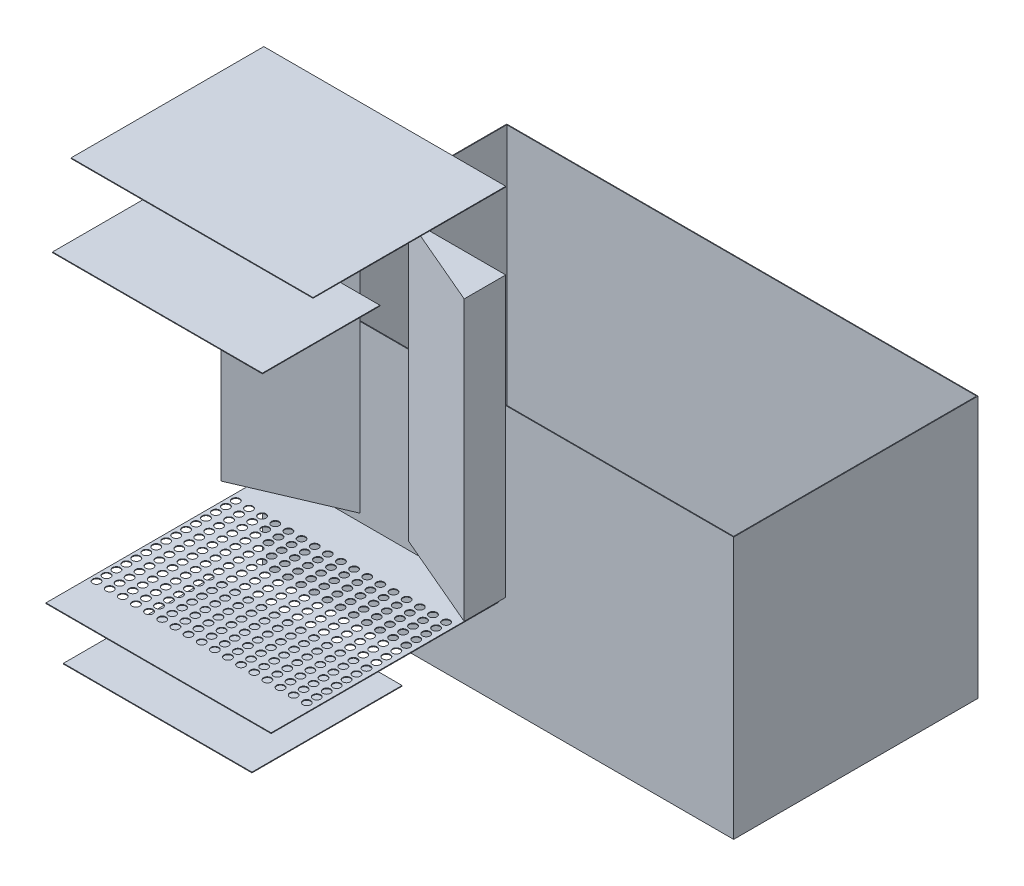
SolidWorks part; units mm, degrees
ref_plane "Спереди" through (0, 0, 0) normal (0, 0, 1) x (1, 0, 0)
ref_plane "Сверху" through (0, 0, 0) normal (0, 1, 0) x (1, 0, 0)
ref_plane "Справа" through (0, 0, 0) normal (1, 0, 0) x (0, 0, -1)
sketch "MASTER_FOOTPRINT" plane through (0, 0, 0) normal (0, 1, 0) x (1, 0, 0)
  line L1 (0, 0) -> (1350, 0)
  line L2 (0, 0) -> (0, 700)
  line L3 (0, 700) -> (1350, 700)
  line L4 (1350, 0) -> (1350, 700)
  dimension "D1" = 1350
  dimension "D2" = 700
extrude "BATH_BASE_PLATE" add sketch "MASTER_FOOTPRINT" along normal blind 750
shell "BATH_SHELL_2MM" thickness 2
sketch "Эскиз1" plane through (0, 0, 0) normal (0, 1, 0) x (1, 0, 0)
  line L1 (80, -220) -> (620, -220)
  line L2 (80, -220) -> (80, -650)
  line L3 (80, -650) -> (620, -650)
  line L4 (620, -220) -> (620, -650)
extrude "INLET_IMPACT_BAFFLE" add sketch "Эскиз1" along normal blind 2 from offset 125 separate body
sketch "Эскиз2" plane through (0, 0, 0) normal (0, 1, 0) x (1, 0, 0)
  line L0 (2, 2) -> (1348, 2) construction
  line L1 (30, 2) -> (675, 2)
  line L2 (30, 2) -> (30, -650)
  line L3 (30, -650) -> (675, -650)
  line L4 (675, 2) -> (675, -650)
  circle A0 centre (48.8235, -125) radius 11
  circle A1 centre (48.8235, -153.5) radius 11
  circle A2 centre (48.8235, -182) radius 11
  circle A3 centre (48.8235, -210.5) radius 11
  circle A4 centre (48.8235, -239) radius 11
  circle A5 centre (48.8235, -267.5) radius 11
  circle A6 centre (48.8235, -296) radius 11
  circle A7 centre (48.8235, -324.5) radius 11
  circle A8 centre (48.8235, -353) radius 11
  circle A9 centre (48.8235, -381.5) radius 11
  circle A10 centre (48.8235, -410) radius 11
  circle A11 centre (48.8235, -438.5) radius 11
  circle A12 centre (48.8235, -467) radius 11
  circle A13 centre (48.8235, -495.5) radius 11
  circle A14 centre (48.8235, -524) radius 11
  circle A15 centre (86.4706, -125) radius 11
  circle A16 centre (86.4706, -153.5) radius 11
  circle A17 centre (86.4706, -182) radius 11
  circle A18 centre (86.4706, -210.5) radius 11
  circle A19 centre (86.4706, -239) radius 11
  circle A20 centre (86.4706, -267.5) radius 11
  circle A21 centre (86.4706, -296) radius 11
  circle A22 centre (86.4706, -324.5) radius 11
  circle A23 centre (86.4706, -353) radius 11
  circle A24 centre (86.4706, -381.5) radius 11
  circle A25 centre (86.4706, -410) radius 11
  circle A26 centre (86.4706, -438.5) radius 11
  circle A27 centre (86.4706, -467) radius 11
  circle A28 centre (86.4706, -495.5) radius 11
  circle A29 centre (86.4706, -524) radius 11
  circle A30 centre (124.1176, -125) radius 11
  circle A31 centre (124.1176, -153.5) radius 11
  circle A32 centre (124.1176, -182) radius 11
  circle A33 centre (124.1176, -210.5) radius 11
  circle A34 centre (124.1176, -239) radius 11
  circle A35 centre (124.1176, -267.5) radius 11
  circle A36 centre (124.1176, -296) radius 11
  circle A37 centre (124.1176, -324.5) radius 11
  circle A38 centre (124.1176, -353) radius 11
  circle A39 centre (124.1176, -381.5) radius 11
  circle A40 centre (124.1176, -410) radius 11
  circle A41 centre (124.1176, -438.5) radius 11
  circle A42 centre (124.1176, -467) radius 11
  circle A43 centre (124.1176, -495.5) radius 11
  circle A44 centre (124.1176, -524) radius 11
  circle A45 centre (161.7647, -125) radius 11
  circle A46 centre (161.7647, -153.5) radius 11
  circle A47 centre (161.7647, -182) radius 11
  circle A48 centre (161.7647, -210.5) radius 11
  circle A49 centre (161.7647, -239) radius 11
  circle A50 centre (161.7647, -267.5) radius 11
  circle A51 centre (161.7647, -296) radius 11
  circle A52 centre (161.7647, -324.5) radius 11
  circle A53 centre (161.7647, -353) radius 11
  circle A54 centre (161.7647, -381.5) radius 11
  circle A55 centre (161.7647, -410) radius 11
  circle A56 centre (161.7647, -438.5) radius 11
  circle A57 centre (161.7647, -467) radius 11
  circle A58 centre (161.7647, -495.5) radius 11
  circle A59 centre (161.7647, -524) radius 11
  circle A60 centre (199.4118, -125) radius 11
  circle A61 centre (199.4118, -153.5) radius 11
  circle A62 centre (199.4118, -182) radius 11
  circle A63 centre (199.4118, -210.5) radius 11
  circle A64 centre (199.4118, -239) radius 11
  circle A65 centre (199.4118, -267.5) radius 11
  circle A66 centre (199.4118, -296) radius 11
  circle A67 centre (199.4118, -324.5) radius 11
  circle A68 centre (199.4118, -353) radius 11
  circle A69 centre (199.4118, -381.5) radius 11
  circle A70 centre (199.4118, -410) radius 11
  circle A71 centre (199.4118, -438.5) radius 11
  circle A72 centre (199.4118, -467) radius 11
  circle A73 centre (199.4118, -495.5) radius 11
  circle A74 centre (199.4118, -524) radius 11
  circle A75 centre (237.0588, -125) radius 11
  circle A76 centre (237.0588, -153.5) radius 11
  circle A77 centre (237.0588, -182) radius 11
  circle A78 centre (237.0588, -210.5) radius 11
  circle A79 centre (237.0588, -239) radius 11
  circle A80 centre (237.0588, -267.5) radius 11
  circle A81 centre (237.0588, -296) radius 11
  circle A82 centre (237.0588, -324.5) radius 11
  circle A83 centre (237.0588, -353) radius 11
  circle A84 centre (237.0588, -381.5) radius 11
  circle A85 centre (237.0588, -410) radius 11
  circle A86 centre (237.0588, -438.5) radius 11
  circle A87 centre (237.0588, -467) radius 11
  circle A88 centre (237.0588, -495.5) radius 11
  circle A89 centre (237.0588, -524) radius 11
  circle A90 centre (274.7059, -125) radius 11
  circle A91 centre (274.7059, -153.5) radius 11
  circle A92 centre (274.7059, -182) radius 11
  circle A93 centre (274.7059, -210.5) radius 11
  circle A94 centre (274.7059, -239) radius 11
  circle A95 centre (274.7059, -267.5) radius 11
  circle A96 centre (274.7059, -296) radius 11
  circle A97 centre (274.7059, -324.5) radius 11
  circle A98 centre (274.7059, -353) radius 11
  circle A99 centre (274.7059, -381.5) radius 11
  circle A100 centre (274.7059, -410) radius 11
  circle A101 centre (274.7059, -438.5) radius 11
  circle A102 centre (274.7059, -467) radius 11
  circle A103 centre (274.7059, -495.5) radius 11
  circle A104 centre (274.7059, -524) radius 11
  circle A105 centre (312.3529, -125) radius 11
  circle A106 centre (312.3529, -153.5) radius 11
  circle A107 centre (312.3529, -182) radius 11
  circle A108 centre (312.3529, -210.5) radius 11
  circle A109 centre (312.3529, -239) radius 11
  circle A110 centre (312.3529, -267.5) radius 11
  circle A111 centre (312.3529, -296) radius 11
  circle A112 centre (312.3529, -324.5) radius 11
  circle A113 centre (312.3529, -353) radius 11
  circle A114 centre (312.3529, -381.5) radius 11
  circle A115 centre (312.3529, -410) radius 11
  circle A116 centre (312.3529, -438.5) radius 11
  circle A117 centre (312.3529, -467) radius 11
  circle A118 centre (312.3529, -495.5) radius 11
  circle A119 centre (312.3529, -524) radius 11
  circle A120 centre (350, -125) radius 11
  circle A121 centre (350, -153.5) radius 11
  circle A122 centre (350, -182) radius 11
  circle A123 centre (350, -210.5) radius 11
  circle A124 centre (350, -239) radius 11
  circle A125 centre (350, -267.5) radius 11
  circle A126 centre (350, -296) radius 11
  circle A127 centre (350, -324.5) radius 11
  circle A128 centre (350, -353) radius 11
  circle A129 centre (350, -381.5) radius 11
  circle A130 centre (350, -410) radius 11
  circle A131 centre (350, -438.5) radius 11
  circle A132 centre (350, -467) radius 11
  circle A133 centre (350, -495.5) radius 11
  circle A134 centre (350, -524) radius 11
  circle A135 centre (387.6471, -125) radius 11
  circle A136 centre (387.6471, -153.5) radius 11
  circle A137 centre (387.6471, -182) radius 11
  circle A138 centre (387.6471, -210.5) radius 11
  circle A139 centre (387.6471, -239) radius 11
  circle A140 centre (387.6471, -267.5) radius 11
  circle A141 centre (387.6471, -296) radius 11
  circle A142 centre (387.6471, -324.5) radius 11
  circle A143 centre (387.6471, -353) radius 11
  circle A144 centre (387.6471, -381.5) radius 11
  circle A145 centre (387.6471, -410) radius 11
  circle A146 centre (387.6471, -438.5) radius 11
  circle A147 centre (387.6471, -467) radius 11
  circle A148 centre (387.6471, -495.5) radius 11
  circle A149 centre (387.6471, -524) radius 11
  circle A150 centre (425.2941, -125) radius 11
  circle A151 centre (425.2941, -153.5) radius 11
  circle A152 centre (425.2941, -182) radius 11
  circle A153 centre (425.2941, -210.5) radius 11
  circle A154 centre (425.2941, -239) radius 11
  circle A155 centre (425.2941, -267.5) radius 11
  circle A156 centre (425.2941, -296) radius 11
  circle A157 centre (425.2941, -324.5) radius 11
  circle A158 centre (425.2941, -353) radius 11
  circle A159 centre (425.2941, -381.5) radius 11
  circle A160 centre (425.2941, -410) radius 11
  circle A161 centre (425.2941, -438.5) radius 11
  circle A162 centre (425.2941, -467) radius 11
  circle A163 centre (425.2941, -495.5) radius 11
  circle A164 centre (425.2941, -524) radius 11
  circle A165 centre (462.9412, -125) radius 11
  circle A166 centre (462.9412, -153.5) radius 11
  circle A167 centre (462.9412, -182) radius 11
  circle A168 centre (462.9412, -210.5) radius 11
  circle A169 centre (462.9412, -239) radius 11
  circle A170 centre (462.9412, -267.5) radius 11
  circle A171 centre (462.9412, -296) radius 11
  circle A172 centre (462.9412, -324.5) radius 11
  circle A173 centre (462.9412, -353) radius 11
  circle A174 centre (462.9412, -381.5) radius 11
  circle A175 centre (462.9412, -410) radius 11
  circle A176 centre (462.9412, -438.5) radius 11
  circle A177 centre (462.9412, -467) radius 11
  circle A178 centre (462.9412, -495.5) radius 11
  circle A179 centre (462.9412, -524) radius 11
  circle A180 centre (500.5882, -125) radius 11
  circle A181 centre (500.5882, -153.5) radius 11
  circle A182 centre (500.5882, -182) radius 11
  circle A183 centre (500.5882, -210.5) radius 11
  circle A184 centre (500.5882, -239) radius 11
  circle A185 centre (500.5882, -267.5) radius 11
  circle A186 centre (500.5882, -296) radius 11
  circle A187 centre (500.5882, -324.5) radius 11
  circle A188 centre (500.5882, -353) radius 11
  circle A189 centre (500.5882, -381.5) radius 11
  circle A190 centre (500.5882, -410) radius 11
  circle A191 centre (500.5882, -438.5) radius 11
  circle A192 centre (500.5882, -467) radius 11
  circle A193 centre (500.5882, -495.5) radius 11
  circle A194 centre (500.5882, -524) radius 11
  circle A195 centre (538.2353, -125) radius 11
  circle A196 centre (538.2353, -153.5) radius 11
  circle A197 centre (538.2353, -182) radius 11
  circle A198 centre (538.2353, -210.5) radius 11
  circle A199 centre (538.2353, -239) radius 11
  circle A200 centre (538.2353, -267.5) radius 11
  circle A201 centre (538.2353, -296) radius 11
  circle A202 centre (538.2353, -324.5) radius 11
  circle A203 centre (538.2353, -353) radius 11
  circle A204 centre (538.2353, -381.5) radius 11
  circle A205 centre (538.2353, -410) radius 11
  circle A206 centre (538.2353, -438.5) radius 11
  circle A207 centre (538.2353, -467) radius 11
  circle A208 centre (538.2353, -495.5) radius 11
  circle A209 centre (538.2353, -524) radius 11
  circle A210 centre (575.8824, -125) radius 11
  circle A211 centre (575.8824, -153.5) radius 11
  circle A212 centre (575.8824, -182) radius 11
  circle A213 centre (575.8824, -210.5) radius 11
  circle A214 centre (575.8824, -239) radius 11
  circle A215 centre (575.8824, -267.5) radius 11
  circle A216 centre (575.8824, -296) radius 11
  circle A217 centre (575.8824, -324.5) radius 11
  circle A218 centre (575.8824, -353) radius 11
  circle A219 centre (575.8824, -381.5) radius 11
  circle A220 centre (575.8824, -410) radius 11
  circle A221 centre (575.8824, -438.5) radius 11
  circle A222 centre (575.8824, -467) radius 11
  circle A223 centre (575.8824, -495.5) radius 11
  circle A224 centre (575.8824, -524) radius 11
  circle A225 centre (613.5294, -125) radius 11
  circle A226 centre (613.5294, -153.5) radius 11
  circle A227 centre (613.5294, -182) radius 11
  circle A228 centre (613.5294, -210.5) radius 11
  circle A229 centre (613.5294, -239) radius 11
  circle A230 centre (613.5294, -267.5) radius 11
  circle A231 centre (613.5294, -296) radius 11
  circle A232 centre (613.5294, -324.5) radius 11
  circle A233 centre (613.5294, -353) radius 11
  circle A234 centre (613.5294, -381.5) radius 11
  circle A235 centre (613.5294, -410) radius 11
  circle A236 centre (613.5294, -438.5) radius 11
  circle A237 centre (613.5294, -467) radius 11
  circle A238 centre (613.5294, -495.5) radius 11
  circle A239 centre (613.5294, -524) radius 11
  circle A240 centre (651.1765, -125) radius 11
  circle A241 centre (651.1765, -153.5) radius 11
  circle A242 centre (651.1765, -182) radius 11
  circle A243 centre (651.1765, -210.5) radius 11
  circle A244 centre (651.1765, -239) radius 11
  circle A245 centre (651.1765, -267.5) radius 11
  circle A246 centre (651.1765, -296) radius 11
  circle A247 centre (651.1765, -324.5) radius 11
  circle A248 centre (651.1765, -353) radius 11
  circle A249 centre (651.1765, -381.5) radius 11
  circle A250 centre (651.1765, -410) radius 11
  circle A251 centre (651.1765, -438.5) radius 11
  circle A252 centre (651.1765, -467) radius 11
  circle A253 centre (651.1765, -495.5) radius 11
  circle A254 centre (651.1765, -524) radius 11
extrude "DISTRIBUTOR_D22" add sketch "Эскиз2" along normal blind 2 from offset 250 separate body
sketch "Эскиз3" plane through (0, 0, 0) normal (0, 1, 0) x (1, 0, 0)
  line L0 (30, -650) -> (675, -650) construction
  line L1 (48.8235, -313.5) -> (650, -313.5)
  line L2 (48.8235, -313.5) -> (48.8235, -650)
  line L3 (48.8235, -650) -> (650, -650)
  line L4 (650, -313.5) -> (650, -650)
  circle A0 centre (48.8235, -324.5) radius 11 construction
extrude "OUTLET_SUBMERGED_BAFFLE" add sketch "Эскиз3" along normal blind 2 from offset 1130 separate body
sketch "Эскиз4" plane through (0, 0, 0) normal (0, 1, 0) x (1, 0, 0)
  line L1 (2, 2) -> (695, 2)
  line L2 (2, 2) -> (2, -550)
  line L3 (2, -550) -> (695, -550)
  line L4 (695, 2) -> (695, -550)
extrude "OVERFLOW_WEIR_Z550" add sketch "Эскиз4" along normal blind 2 from offset 1290 separate body
sketch "Эскиз5" plane through (0, 0, 0) normal (0, 1, 0) x (1, 0, 0)
  line L0 (2, -1) -> (2, -120)
  line L1 (2, -120) -> (280, -1)
  line L2 (280, -1) -> (2, -1)
  line L3 (698, -1) -> (698, -120)
  line L4 (698, -120) -> (420, -1)
  line L5 (420, -1) -> (698, -1)
extrude "SLOPED_SEDIMENT_FLOOR" add sketch "Эскиз5" along normal blind 800 from offset 275
equation "\"AI_Q_Peak\"= 0.006"
equation "\"AI_B_Bath\"= 700"
equation "\"AI_L_Settle\"= 900"
equation "\"AI_L_Inlet\"= 250"
equation "\"AI_L_Outlet\"= 200"
equation "\"AI_L_Bath\"= 1350"
equation "\"AI_H_Water\"= 550"
equation "\"AI_H_Freeboard\"= 200"
equation "\"AI_H_Bath\"= 750"
equation "\"AI_Shell_Thickness\"= 2"
equation "\"AI_Inlet_DN\"= 100"
equation "\"AI_Weir_Width\"= 600"
equation "\"AI_Inlet_Baffle_Offset\"= 125"
equation "\"AI_Distributor_Open_Area\"= 0.28"
equation "\"AI_Distributor_Hole_Dia\"= 22"
equation "\"AI_Distributor_Blind_Zone\"= 110"
equation "\"AI_Outlet_Baffle_Depth\"= 250"
equation "\"AI_Screw_Diameter\"= 100"
equation "\"AI_Screw_Pitch\"= 100"
equation "\"AI_Screw_Angle\"= 30"
equation "\"AI_Screw_Rpm\"= 15"
equation "\"AI_Screw_Clearance\"= 5"
equation "\"AI_Liner_Thickness\"= 5"
equation "\"AI_Discharge_Height\"= 650"
equation "\"AI_Frame_Height\"= 500"
equation "\"D1@MASTER_FOOTPRINT\" = \"AI_L_Bath\""
equation "\"D2@MASTER_FOOTPRINT\" = \"AI_B_Bath\""
equation "\"D1@BATH_BASE_PLATE\" = \"AI_H_Bath\""
